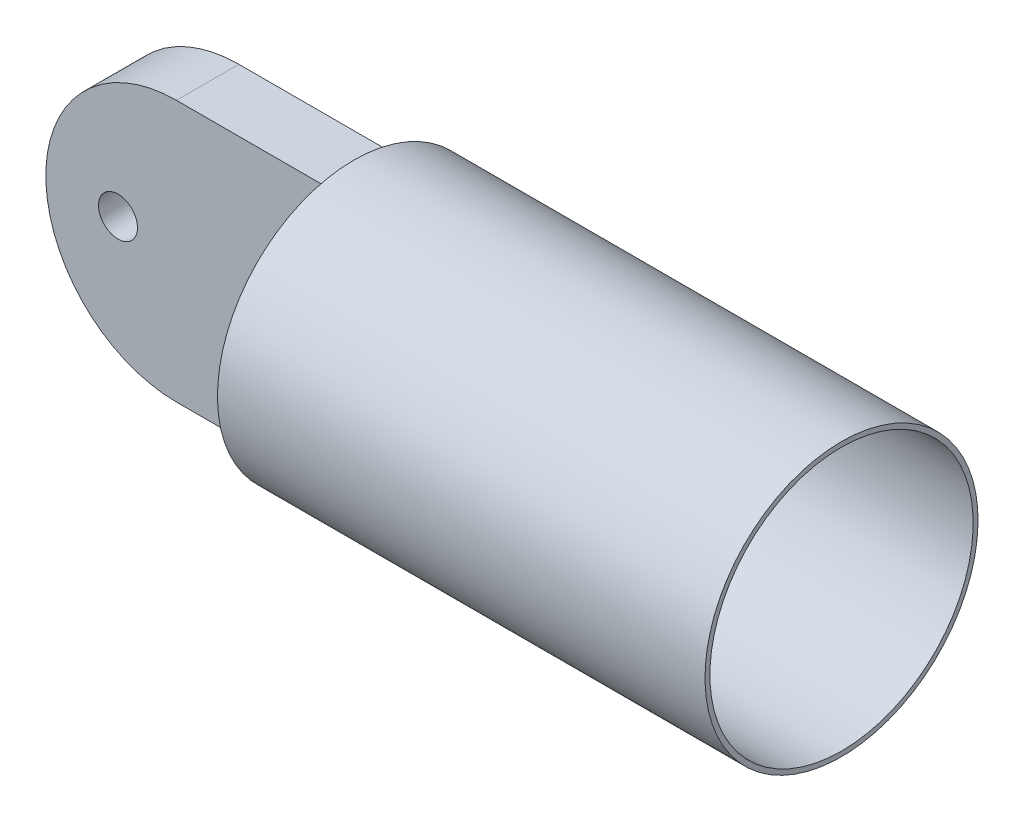
SolidWorks part; units mm, degrees
ref_plane "前视基准面" through (0, 0, 0) normal (0, 0, 1) x (1, 0, 0)
ref_plane "上视基准面" through (0, 0, 0) normal (0, 1, 0) x (1, 0, 0)
ref_plane "右视基准面" through (0, 0, 0) normal (1, 0, 0) x (0, 0, -1)
sketch "草图1" plane through (0, 0, 0) normal (0, 0, 1) x (1, 0, 0)
  line L0 (-567.0596, 207.6014) -> (-417.0596, 207.6014)
  line L1 (-567.0596, 475.6014) -> (-417.0596, 475.6014)
  line L2 (-417.0596, 475.6014) -> (-417.0596, 207.6014)
  arc A0 (-567.0596, 207.6014) -> (-567.0596, 475.6014) centre (-567.0596, 341.6014) cw
  dimension "D1" = 134
  dimension "D2" = 150
  dimension "D3" = 150
extrude "凸台-拉伸1" add sketch "草图1" along normal blind 64
sketch "草图2" plane through (0, 0, 64) normal (0, 0, 1) x (1, 0, 0)
  circle A0 centre (-627.0596, 342.3875) radius 20
  arc A1 (-567.0596, 475.6014) -> (-567.0596, 207.6014) centre (-567.0596, 341.6014) ccw construction
  dimension "D1" = 40
  dimension "D2" = 60
extrude "切除-拉伸1" cut sketch "草图2" against normal through all both and the other way through all
sketch "草图4" plane through (-417.0596, 0, 0) normal (1, 0, 0) x (0, 0, -1)
  line L0 (0, 207.6014) -> (0, 475.6014) construction
  line L1 (-64, 207.6014) -> (0, 207.6014) construction
  circle A0 centre (-32, 341.6014) radius 140
  dimension "D3" = 280
  dimension "D1" = 32
  dimension "D2" = 134
extrude "凸台-拉伸4" add sketch "草图4" along normal blind 500
shell "抽壳6" thickness 5
